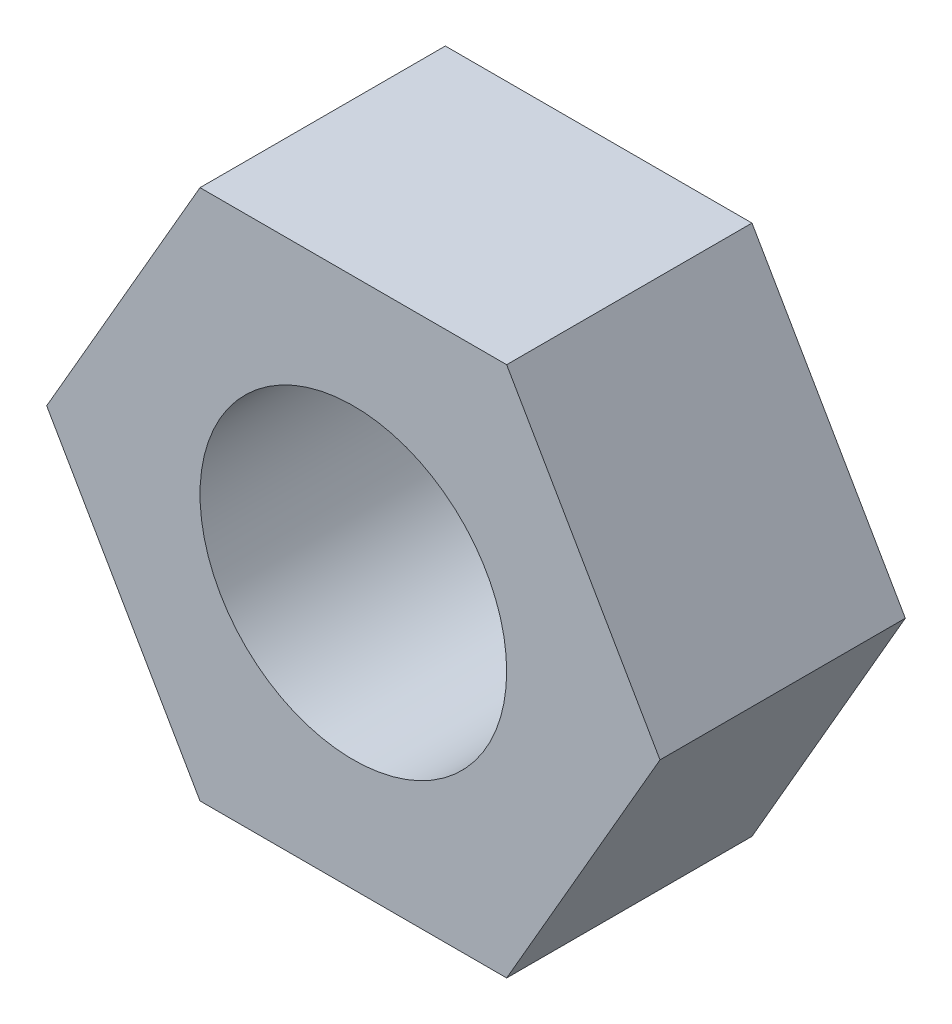
SolidWorks part; units mm, degrees
ref_plane "Front Plane" through (0, 0, 0) normal (0, 0, 1) x (1, 0, 0)
ref_plane "Top Plane" through (0, 0, 0) normal (0, 1, 0) x (1, 0, 0)
ref_plane "Right Plane" through (0, 0, 0) normal (1, 0, 0) x (0, 0, -1)
sketch "Sketch1" plane through (0, 0, 0) normal (0, 0, 1) x (1, 0, 0)
  line L1 (5, 0) -> (2.5, 4.3301)
  line L2 (2.5, 4.3301) -> (-2.5, 4.3301)
  line L3 (-2.5, 4.3301) -> (-5, 0)
  line L4 (-5, 0) -> (-2.5, -4.3301)
  line L5 (-2.5, -4.3301) -> (2.5, -4.3301)
  line L6 (2.5, -4.3301) -> (5, 0)
  circle A0 centre (0, 0) radius 4.3301 construction
  dimension "D1" = 10
extrude "Boss-Extrude1" add sketch "Sketch1" along normal blind 4
sketch "Sketch2" plane through (0, 0, 4) normal (0, 0, 1) x (1, 0, 0)
  circle A0 centre (0, 0) radius 2.5
  point P3 (0, 0)
  dimension "D1" = 5
extrude "Cut-Extrude1" cut sketch "Sketch2" against normal through all contours A0
